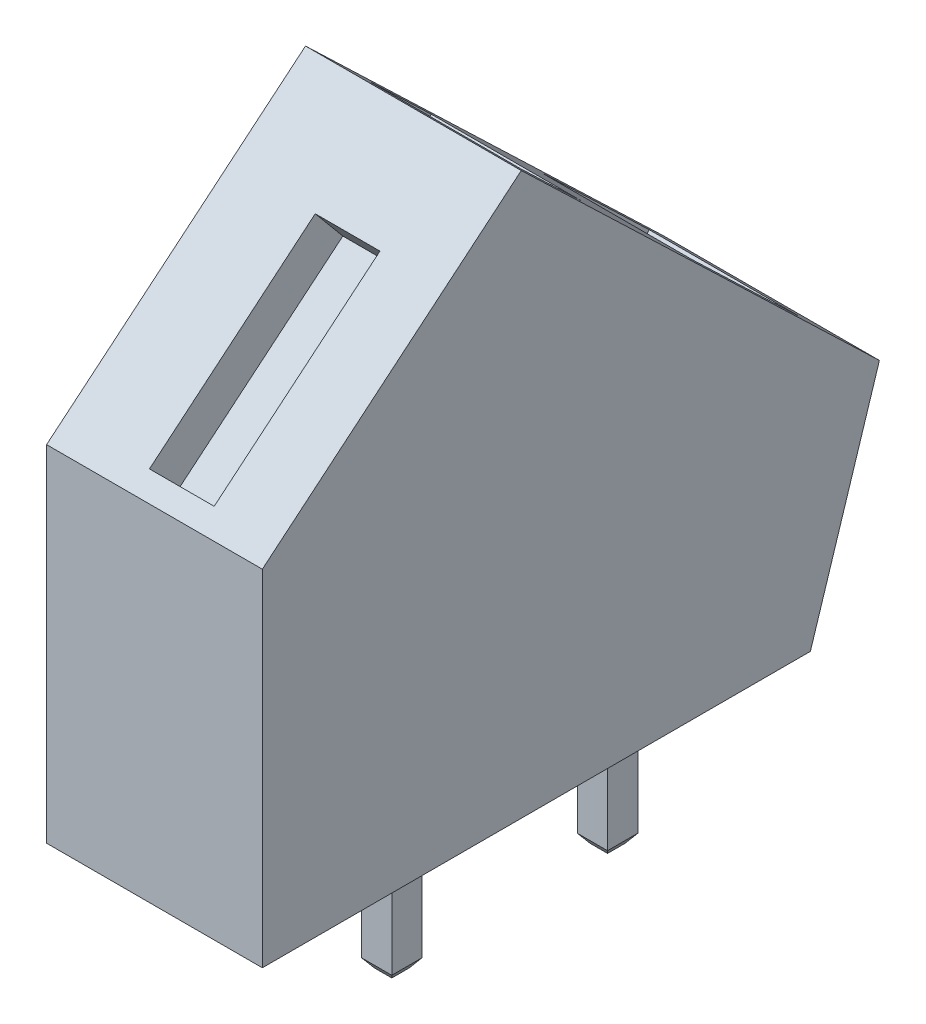
SolidWorks part; units mm, degrees
ref_plane "Спереди" through (0, 0, 0) normal (0, 0, 1) x (1, 0, 0)
ref_plane "Сверху" through (0, 0, 0) normal (0, 1, 0) x (1, 0, 0)
ref_plane "Справа" through (0, 0, 0) normal (1, 0, 0) x (0, 0, -1)
sketch "Эскиз2" plane through (0, 0, 0) normal (1, 0, 0) x (0, -1, 0)
  line L0 (0, -6.35) -> (0, 6.35)
  line L4 (0, -6.35) -> (-8, -6.35)
  line L5 (-8, -6.35) -> (-13, -0.35)
  line L6 (-13, -0.35) -> (-5.0401, 7.95)
  line L7 (-5.0401, 7.95) -> (0, 6.35)
  dimension "D1" = 14.3
  dimension "D2" = 12.7
  dimension "D3" = 6
  dimension "D4" = 8
  dimension "D5" = 5.0401
  dimension "D6" = 13
extrude "Бобышка-Вытянуть2" add sketch "Эскиз2" along normal mid plane 5
sketch "Эскиз4" plane through (0, 6.5969, -6.3266) normal (0, 0.7217, -0.6922) x (1, 0, 0)
  line L0 (0, -7.15) -> (0, 7.15) construction
  line L1 (1.75, -8.2508) -> (-1.75, -8.2508)
  line L2 (1.75, -8.2508) -> (1.75, -6.2508)
  line L3 (1.75, -6.2508) -> (-1.75, -6.2508)
  line L4 (-1.75, -8.2508) -> (-1.75, -6.2508)
  line L5 (1.75, -8.2508) -> (-1.75, -6.2508) construction
  line L6 (1.75, -6.2508) -> (-1.75, -8.2508) construction
  line L7 (-1.75, 0.7492) -> (1.75, 0.7492)
  line L8 (-1.75, 0.7492) -> (-1.75, -2.7508)
  line L9 (-1.75, -2.7508) -> (1.75, -2.7508)
  line L10 (1.75, 0.7492) -> (1.75, -2.7508)
  line L11 (-1.75, 0.7492) -> (1.75, -2.7508) construction
  line L12 (-1.75, -2.7508) -> (1.75, 0.7492) construction
  line L13 (2.5, 2.2492) -> (2.5, -9.2508) construction
  line L14 (2.5, -9.2508) -> (-2.5, -9.2508) construction
  point P0 (0, -7.2508)
  point P5 (0, -1.0008)
  point P10 (0, 0)
  point P13 (0, 0)
  point P14 (0, 0)
  point P15 (0, 0)
  dimension "D1" = 0.75
  dimension "D2" = 1
  dimension "D3" = 2
  dimension "D4" = 3.5
  dimension "D5" = 3.5
extrude "Вырез-Вытянуть1" cut sketch "Эскиз4" against normal blind 1
sketch "Эскиз5" plane through (0, 7.8443, 6.5369) normal (0, 0.7682, 0.6402) x (1, 0, 0)
  line L0 (2.5, 8.0535) -> (2.5, 0.2433) construction
  line L1 (-0.5, 5.7433) -> (1, 5.7433)
  line L2 (-0.5, 5.7433) -> (-0.5, 0.7433)
  line L3 (-0.5, 0.7433) -> (1, 0.7433)
  line L4 (1, 5.7433) -> (1, 0.7433)
  line L5 (-0.5, 5.7433) -> (1, 0.7433) construction
  line L6 (-0.5, 0.7433) -> (1, 5.7433) construction
  line L7 (-2.5, 8.0535) -> (-2.5, 0.2433) construction
  line L8 (2.5, 0.2433) -> (-2.5, 0.2433) construction
  point P0 (0.25, 3.2433)
  dimension "D1" = 1.5
  dimension "D2" = 2
  dimension "D3" = 0.5
  dimension "D4" = 5
extrude "Вырез-Вытянуть2" cut sketch "Эскиз5" against normal blind 1
sketch "Эскиз6" plane through (0, 0, 0) normal (0, -1, 0) x (1, 0, 0)
  line L0 (2.5, 6.35) -> (-2.5, 6.35) construction
  line L1 (0.85, 1.7) -> (0.15, 1.7)
  line L2 (0.85, 1.7) -> (0.85, 1)
  line L3 (0.85, 1) -> (0.15, 1)
  line L4 (0.15, 1.7) -> (0.15, 1)
  line L5 (0.85, 1.7) -> (0.15, 1) construction
  line L6 (0.85, 1) -> (0.15, 1.7) construction
  line L7 (0.85, -3.3) -> (0.15, -3.3)
  line L8 (0.85, -3.3) -> (0.85, -4)
  line L9 (0.85, -4) -> (0.15, -4)
  line L10 (0.15, -3.3) -> (0.15, -4)
  line L11 (0.85, -3.3) -> (0.15, -4) construction
  line L12 (0.85, -4) -> (0.15, -3.3) construction
  line L14 (-2.5, 6.35) -> (-2.5, -6.35) construction
  point P0 (0.5, 1.35)
  point P5 (0.5, -3.65)
  point P12 (0, 0)
  point P13 (0, 0)
  point P15 (0, 0)
  point P16 (0, 0)
  point P17 (0, 0)
  dimension "D1" = 5
  dimension "D2" = 5
  dimension "D3" = 0.7
  dimension "D4" = 3
extrude "Бобышка-Вытянуть3" add sketch "Эскиз6" along normal blind 3.5
chamfer "Фаска3" distance 0.2 angle 36 8 edges at (0.5, -3.5, -4) (0.85, -3.5, -3.65) (0.5, -3.5, -3.3) (0.15, -3.5, -3.65) (0.5, -3.5, 1) (0.15, -3.5, 1.35) (0.5, -3.5, 1.7) (0.85, -3.5, 1.35)
